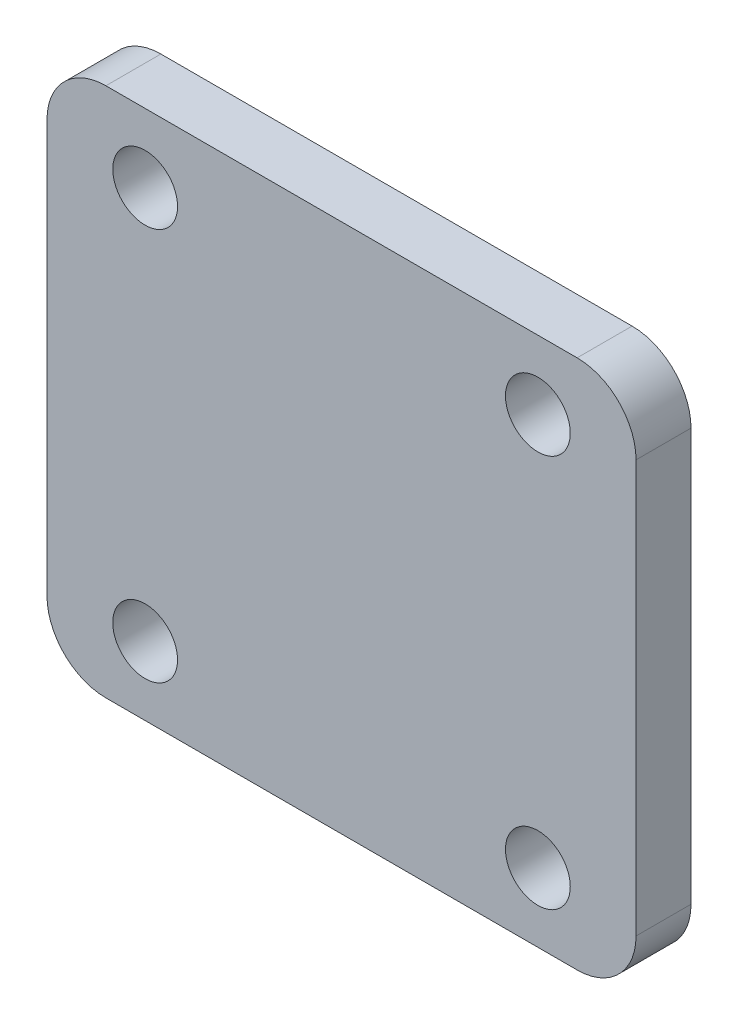
SolidWorks part; units mm, degrees
ref_plane "前视基准面" through (0, 0, 0) normal (0, 0, 1) x (1, 0, 0)
ref_plane "上视基准面" through (0, 0, 0) normal (0, 1, 0) x (1, 0, 0)
ref_plane "右视基准面" through (0, 0, 0) normal (1, 0, 0) x (0, 0, -1)
other "Configuration Table"
sketch "草图1" plane through (0, 0, 0) normal (0, 0, 1) x (1, 0, 0)
  line L0 (15, 27) -> (15, -8.0674) construction
  line L1 (0, 0) -> (30, 0)
  line L2 (0, 0) -> (0, 27)
  line L3 (0, 27) -> (30, 27)
  line L4 (30, 0) -> (30, 27)
  line L5 (0, 13.5) -> (48.9969, 13.5) construction
  circle A0 centre (5, 23.5) radius 1.65
  circle A1 centre (25, 23.5) radius 1.65
  circle A2 centre (25, 3.5) radius 1.65
  circle A3 centre (5, 3.5) radius 1.65
  dimension "D3" = 3.3
  dimension "D4" = 20
  dimension "D5" = 20
  dimension "D1" = 30
  dimension "D2" = 27
extrude "凸台-拉伸1" add sketch "草图1" along normal blind 2.8
fillet "圆角1" radius 3 4 edges at (0, 27, 1.4) (30, 0, 1.4) (0, 0, 1.4) (30, 27, 1.4)
